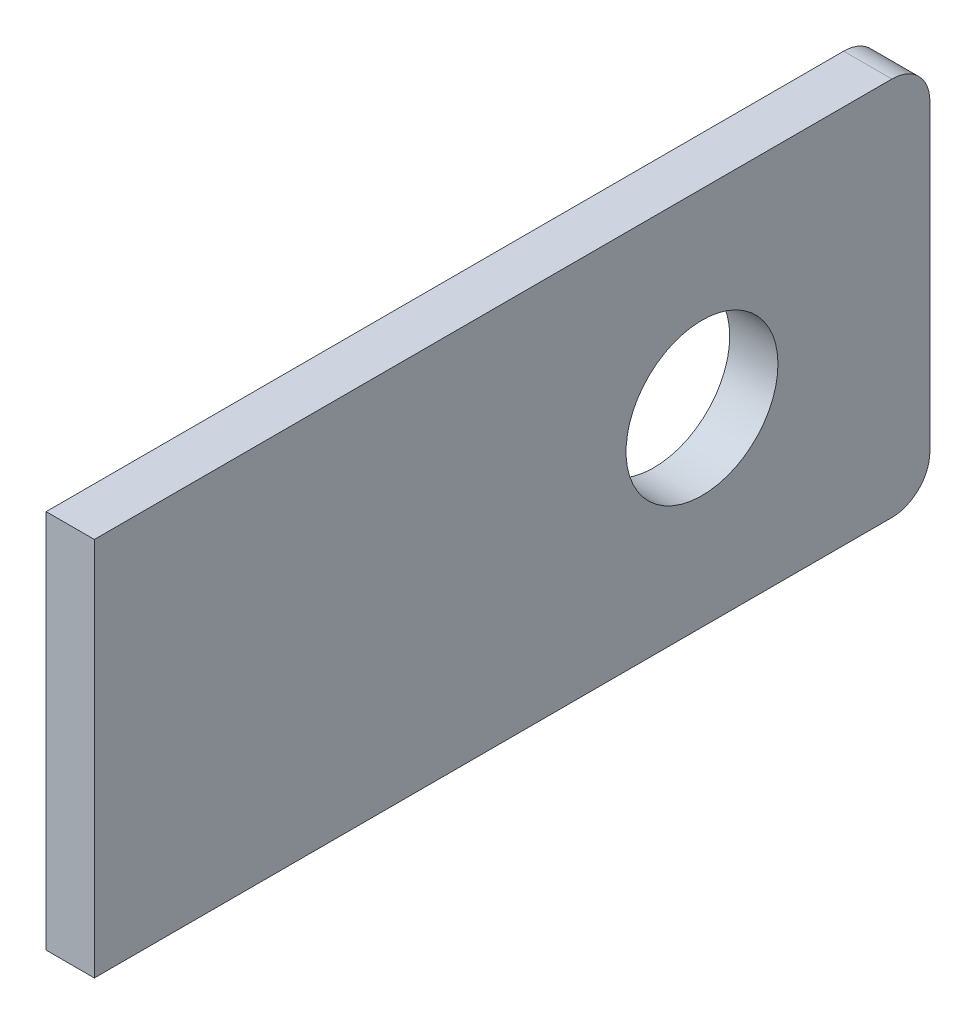
SolidWorks part; units mm, degrees
ref_plane "Front Plane" through (0, 0, 0) normal (0, 0, 1) x (1, 0, 0)
ref_plane "Top Plane" through (0, 0, 0) normal (0, 1, 0) x (1, 0, 0)
ref_plane "Right Plane" through (0, 0, 0) normal (1, 0, 0) x (0, 0, -1)
sketch "Sketch1" plane through (0, 0, 0) normal (1, 0, 0) x (0, 0, -1)
  line L1 (-80, 25) -> (30, 25)
  line L2 (-80, 25) -> (-80, -25)
  line L3 (-80, -25) -> (30, -25)
  line L4 (30, 25) -> (30, -25)
  line L5 (-80, 25) -> (30, -25) construction
  line L6 (-80, -25) -> (30, 25) construction
  circle A0 centre (0, 0) radius 10
  point P3 (-25, 0)
  dimension "D1" = 20
  dimension "D2" = 80
  dimension "D3" = 110
  dimension "D4" = 50
extrude "Boss-Extrude1" add sketch "Sketch1" along normal mid plane 6.35
fillet "Fillet1" radius 5 2 edges at (0, -25, -30) (0, 25, -30)
